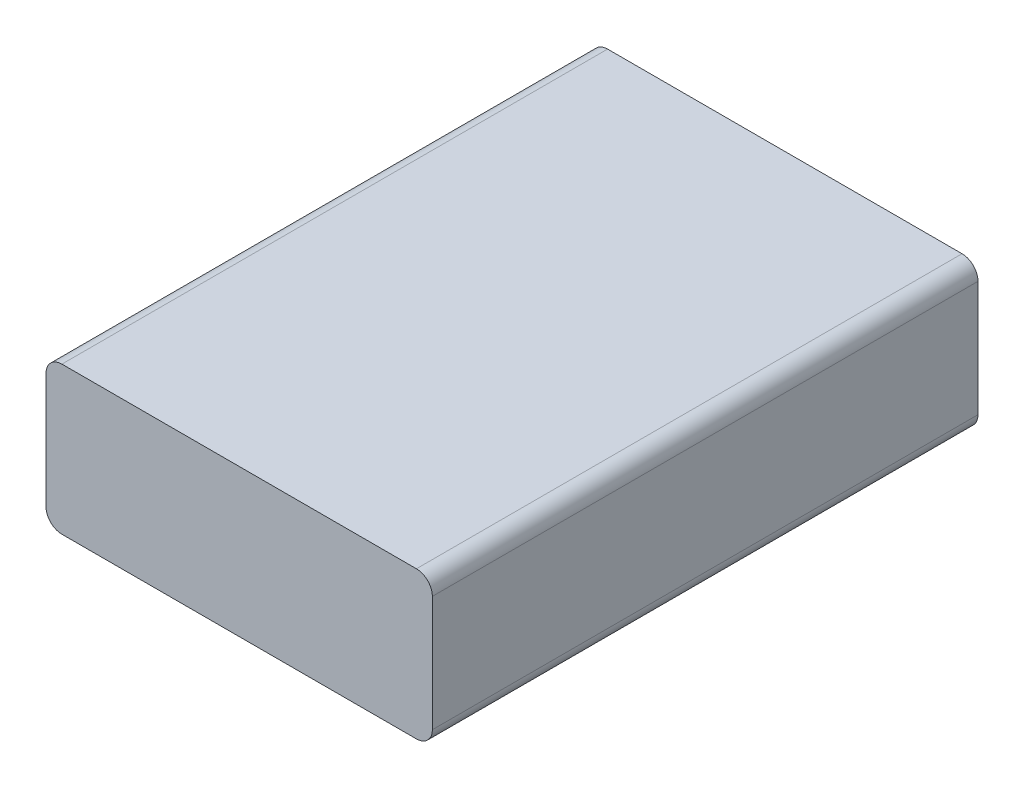
SolidWorks part; units mm, degrees
material "Malleable Cast Iron"
ref_plane "Front Plane" through (0, 0, 0) normal (0, 0, 1) x (1, 0, 0)
ref_plane "Top Plane" through (0, 0, 0) normal (0, 1, 0) x (1, 0, 0)
ref_plane "Right Plane" through (0, 0, 0) normal (1, 0, 0) x (0, 0, -1)
sketch "Sketch1" plane through (0, 0, 0) normal (0, 1, 0) x (1, 0, 0)
  line L1 (-24.25, -34.25) -> (24.25, -34.25)
  line L2 (-24.25, -34.25) -> (-24.25, 34.25)
  line L3 (-24.25, 34.25) -> (24.25, 34.25)
  line L4 (24.25, -34.25) -> (24.25, 34.25)
  line L5 (-24.25, -34.25) -> (24.25, 34.25) construction
  line L6 (-24.25, 34.25) -> (24.25, -34.25) construction
  point P0 (0, 0)
  dimension "D1" = 68.5
  dimension "D2" = 48.5
extrude "Boss-Extrude1" add sketch "Sketch1" along normal blind 18.5
fillet "Fillet1" radius 2 4 edges at (-24.25, 0, 0) (24.25, 0, 0) (-24.25, 18.5, 0) (24.25, 18.5, 0)
